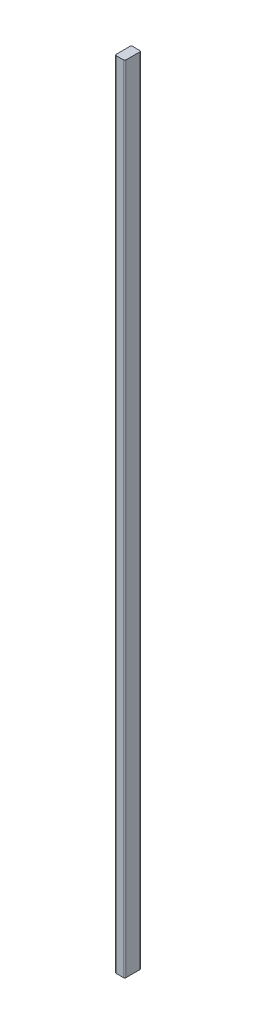
SolidWorks part; units mm, degrees
material "Hexcel AS4C (3000 Filaments)"
ref_plane "Front Plane" through (0, 0, 0) normal (0, 0, 1) x (1, 0, 0)
ref_plane "Top Plane" through (0, 0, 0) normal (0, 1, 0) x (1, 0, 0)
ref_plane "Right Plane" through (0, 0, 0) normal (1, 0, 0) x (0, 0, -1)
sketch "Sketch1" plane through (0, 0, 0) normal (0, 1, 0) x (1, 0, 0)
  line L1 (2.25, 5) -> (-2.25, 5)
  line L2 (3, 4.25) -> (3, -4.25)
  line L3 (2.25, -5) -> (-2.25, -5)
  line L4 (-3, 4.25) -> (-3, -4.25)
  line L5 (3, 5) -> (-3, -5) construction
  line L6 (3, -5) -> (-3, 5) construction
  arc A0 (2.25, -5) -> (3, -4.25) centre (2.25, -4.25) ccw
  arc A1 (2.25, 5) -> (3, 4.25) centre (2.25, 4.25) cw
  arc A2 (-2.25, 5) -> (-3, 4.25) centre (-2.25, 4.25) ccw
  arc A3 (-3, -4.25) -> (-2.25, -5) centre (-2.25, -4.25) ccw
  point P0 (0, 0)
  dimension "D3" = 0.75
  dimension "D1" = 6
  dimension "D2" = 10
extrude "Boss-Extrude1" add sketch "Sketch1" along normal blind 489
